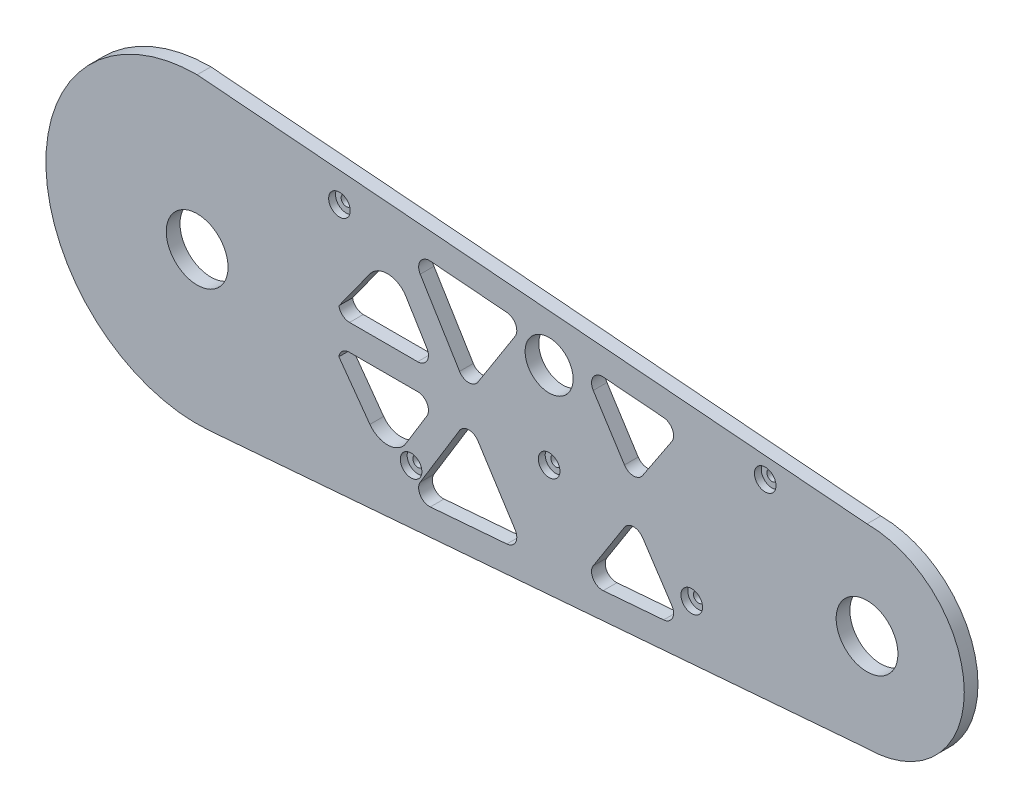
SolidWorks part; units mm, degrees
other "Marca1"
sketch "Croquis3" plane through (-70, -70, 6.35) normal (0, 0, 1) x (1, 0, 0)
material "6061-O (SS)"
ref_plane "Front Plane" through (0, 0, 0) normal (0, 0, 1) x (1, 0, 0)
ref_plane "Top Plane" through (0, 0, 0) normal (0, 1, 0) x (1, 0, 0)
ref_plane "Right Plane" through (0, 0, 0) normal (1, 0, 0) x (0, 0, -1)
sketch "Sketch1" plane through (0, 0, 0) normal (0, 0, 1) x (1, 0, 0)
  line L0 (0, 70) -> (310, 45)
  line L1 (5.1714, -69.8087) -> (310, -45)
  line L2 (0, 0) -> (310, 0) construction
  line L3 (107.899, 49.2595) -> (143.3142, 46.4034)
  line L4 (70.5232, 6) -> (102.03, 6)
  line L5 (219.6238, 32.8105) -> (206.1309, 12.4175)
  line L6 (197.7459, 12.4871) -> (183.2969, 35.1335)
  line L7 (162.8785, 6) -> (162.8785, -6) construction
  line L8 (258.6323, 64.5867) -> (258.6323, 39.5867) construction
  line L9 (147.1275, 38.7303) -> (129.9162, 11.7546)
  line L10 (121.433, 11.8395) -> (103.229, 41.6712)
  line L11 (98.117, 50.0484) -> (42.0027, 50.0484) construction
  line L12 (187.9139, 42.8067) -> (215.8558, 40.5533)
  line L13 (162.8785, 44.8257) -> (162.8785, 6) construction
  line L14 (67.1248, 64.5867) -> (162.8785, 35) construction
  line L15 (201.8849, 6) -> (201.8849, 41.68) construction
  line L16 (125.6066, 5) -> (125.6066, 47.8315) construction
  line L17 (96.5904, 29.5131) -> (106.2981, 13.6045)
  line L18 (125.6066, -5) -> (125.6066, -47.8315) construction
  line L19 (201.8849, -6) -> (201.8849, -41.68) construction
  line L20 (162.8785, -44.8257) -> (162.8785, -6) construction
  line L21 (98.117, -50.0484) -> (42.0027, -50.0484) construction
  line L22 (96.5904, -29.5131) -> (106.2981, -13.6045)
  line L23 (67.1248, 64.5867) -> (409.6974, 64.5867) construction
  line L24 (187.9139, -42.8067) -> (215.8558, -40.5533)
  line L25 (121.433, -11.8395) -> (103.229, -41.6712)
  line L26 (147.1275, -38.7303) -> (129.9162, -11.7546)
  line L27 (162.8785, 0) -> (258.6323, 64.5867) construction
  line L28 (67.1248, 64.5867) -> (67.1248, 39.5867) construction
  line L29 (197.7459, -12.4871) -> (183.2969, -35.1335)
  line L30 (219.6238, -32.8105) -> (206.1309, -12.4175)
  line L31 (70.5232, -6) -> (102.03, -6)
  line L32 (107.899, -49.2595) -> (143.3142, -46.4034)
  line L33 (0, -6.35) -> (0, 6.35) construction
  line L34 (67.1248, 39.5867) -> (162.8785, 35) construction
  line L35 (162.8785, 35) -> (67.6719, 24.0904) construction
  line L36 (79.9417, 30.1512) -> (65.583, 10.2294)
  line L37 (79.9417, -30.1512) -> (65.583, -10.2294)
  arc A0 (65.583, 10.2294) -> (70.5232, 6) centre (70.5232, 11) ccw
  arc A1 (310, -45) -> (310, 45) centre (310, 0) ccw
  circle A2 centre (0, 0) radius 14.2938
  circle A3 centre (310, 0) radius 14.2939
  arc A4 (79.9417, 30.1512) -> (96.5904, 29.5131) centre (88.0542, 24.3041) cw
  arc A5 (79.9417, -30.1512) -> (96.5904, -29.5131) centre (88.0542, -24.3041) ccw
  arc A6 (0, 70) -> (5.1714, -69.8087) centre (0, 0) ccw
  arc A7 (187.9139, 42.8067) -> (183.2969, 35.1335) centre (187.512, 37.8229) ccw
  arc A8 (219.6238, 32.8105) -> (215.8558, 40.5533) centre (215.4539, 35.5695) ccw
  arc A9 (206.1309, 12.4175) -> (197.7459, 12.4871) centre (201.961, 15.1765) cw
  circle A10 centre (162.8785, 35) radius 11.1125
  arc A13 (102.03, 6) -> (106.2981, 13.6045) centre (102.03, 11) ccw
  arc A14 (121.433, 11.8395) -> (129.9162, 11.7546) centre (125.7011, 14.444) ccw
  arc A15 (147.1275, 38.7303) -> (143.3142, 46.4034) centre (142.9123, 41.4196) ccw
  arc A16 (107.899, 49.2595) -> (103.229, 41.6712) centre (107.4971, 44.2757) ccw
  arc A17 (107.899, -49.2595) -> (103.229, -41.6712) centre (107.4971, -44.2757) cw
  arc A18 (147.1275, -38.7303) -> (143.3142, -46.4034) centre (142.9123, -41.4196) cw
  arc A19 (121.433, -11.8395) -> (129.9162, -11.7546) centre (125.7011, -14.444) cw
  arc A20 (102.03, -6) -> (106.2981, -13.6045) centre (102.03, -11) cw
  arc A24 (206.1309, -12.4175) -> (197.7459, -12.4871) centre (201.961, -15.1765) ccw
  arc A25 (219.6238, -32.8105) -> (215.8558, -40.5533) centre (215.4539, -35.5695) cw
  arc A26 (187.9139, -42.8067) -> (183.2969, -35.1335) centre (187.512, -37.8229) cw
  arc A29 (65.583, -10.2294) -> (70.5232, -6) centre (70.5232, -11) cw
  point P31 (177.8851, 43.6155)
  point P42 (187.6504, 6)
  point P44 (88.7465, 42.3671)
  point P45 (138.1067, 6)
  point P79 (88.7465, -42.3671)
  point P100 (138.1067, -6)
  point P101 (187.6504, -6)
  point P102 (177.8851, -43.6155)
  point P104 (0, 0)
  point P114 (310, 0)
  point P119 (0.2114, 0.3175)
  dimension "D2" = 45
  dimension "D3" = 12.7
  dimension "D4" = 28.5877
  dimension "D6" = 12
  dimension "D11" = 5
  dimension "D12" = 70
  dimension "D13" = 25
  dimension "D8" = 5
  dimension "D14" = 12
  dimension "D15" = 25
  dimension "D16" = 310
  dimension "D17" = 22.225
  dimension "D5" = 28.5877
  dimension "D19" = 10
  dimension "D20" = 10
  dimension "D7" = 6
  dimension "D9" = 9.279
  dimension "D10" = 34
  dimension "D18" = 35
extrude "Boss-Extrude1" add sketch "Sketch1" along normal blind 6.35
sketch "Sketch2" plane through (0, 0, 6.35) normal (0, 0, 1) x (1, 0, 0)
  line L0 (263.0927, 39.4927) -> (-0.4655, 64.9983)
  line L1 (4.6885, -64.8307) -> (263.1366, -39.5384)
  arc A0 (-0.4655, 64.9983) -> (4.6885, -64.8307) centre (0, 0) ccw
  arc A1 (263.1366, -39.5384) -> (270.3186, -23.7999) centre (262.1626, -29.5859) ccw
  circle A2 centre (0, 0) radius 40
  arc A3 (270.292, 23.7623) -> (270.3186, -23.7999) centre (303.867, 0) ccw
  arc A4 (270.292, 23.7623) -> (263.0927, 39.4927) centre (262.1295, 29.5392) ccw
  dimension "D1" = 10
  dimension "D2" = 41.133
  dimension "D3" = 65
ref_plane "Plane1" through (0, 0, 10) normal (0, 0, 1) x (1, 0, 0)
sketch "Croquis1" plane through (0, 0, 6.35) normal (0, 0, 1) x (1, 0, 0)
  circle A1 centre (98.9956, -37.0901) radius 2.3813
  circle A2 centre (228.8774, -26.5196) radius 2.3813
  point P20 (0, 0)
  dimension "D5" = 4.7625
  dimension "D1" = 4.7625
extrude "Cortar-Extruir1" cut sketch "Croquis1" against normal blind 50
sketch "Croquis4" plane through (0, 0, 0) normal (0, 0, -1) x (-1, 0, 0)
  circle A0 centre (-228.8774, -26.5196) radius 5
  circle A1 centre (-98.9956, -37.0901) radius 5
  dimension "D1" = 10
sketch "Croquis5" plane through (0, 0, 0) normal (0, 0, -1) x (-1, 0, 0)
  line L0 (-162.8785, 35) -> (-162.8785, -35.6506) construction
  line L1 (-193.2674, -35.6506) -> (-132.4897, -35.6506) construction
  circle A0 centre (-162.8785, -5) radius 5
  point P6 (-162.8785, -35.6506)
  dimension "D2" = 10
  dimension "D1" = 40
sketch "Croquis6" plane through (0, 0, 0) normal (0, 0, -1) x (-1, 0, 0)
  circle A0 centre (-162.8785, -5) radius 2.3813
  dimension "D1" = 4.7625
extrude "Cortar-Extruir4" cut sketch "Croquis6" against normal blind 10
sketch "Croquis7" plane through (0, 0, 0) normal (0, 0, -1) x (-1, 0, 0)
  line L0 (-228.8774, -26.5196) -> (-98.9956, -37.0901) construction
  line L1 (-98.9956, -37.0901) -> (-65.8414, 50.869) construction
  line L2 (-228.8774, -26.5196) -> (-262.8716, 39.2101) construction
  circle A0 centre (-65.8414, 50.869) radius 2.3813
  circle A1 centre (-262.8716, 39.2101) radius 2.3813
  dimension "D5" = 4.7625
  dimension "D1" = 94
  dimension "D2" = 106
  dimension "D3" = 74
  dimension "D4" = 238
extrude "Cortar-Extruir5" cut sketch "Croquis7" against normal blind 10
sketch "Croquis8" plane through (0, 0, 0) normal (0, 0, -1) x (-1, 0, 0)
  circle A0 centre (-262.8716, 39.2101) radius 5
  circle A1 centre (-65.8414, 50.869) radius 5
  dimension "D1" = 10
  dimension "D2" = 10
sketch "Croquis9" plane through (0, 0, 6.35) normal (0, 0, 1) x (1, 0, 0)
  circle A0 centre (65.8414, 50.869) radius 5
  circle A1 centre (162.8785, -5) radius 5
  circle A2 centre (98.9956, -37.0901) radius 5
  circle A3 centre (228.8774, -26.5196) radius 5
  circle A4 centre (262.8716, 39.2101) radius 5
  dimension "D1" = 10
extrude "Cortar-Extruir6" cut sketch "Croquis9" against normal blind 3.18
